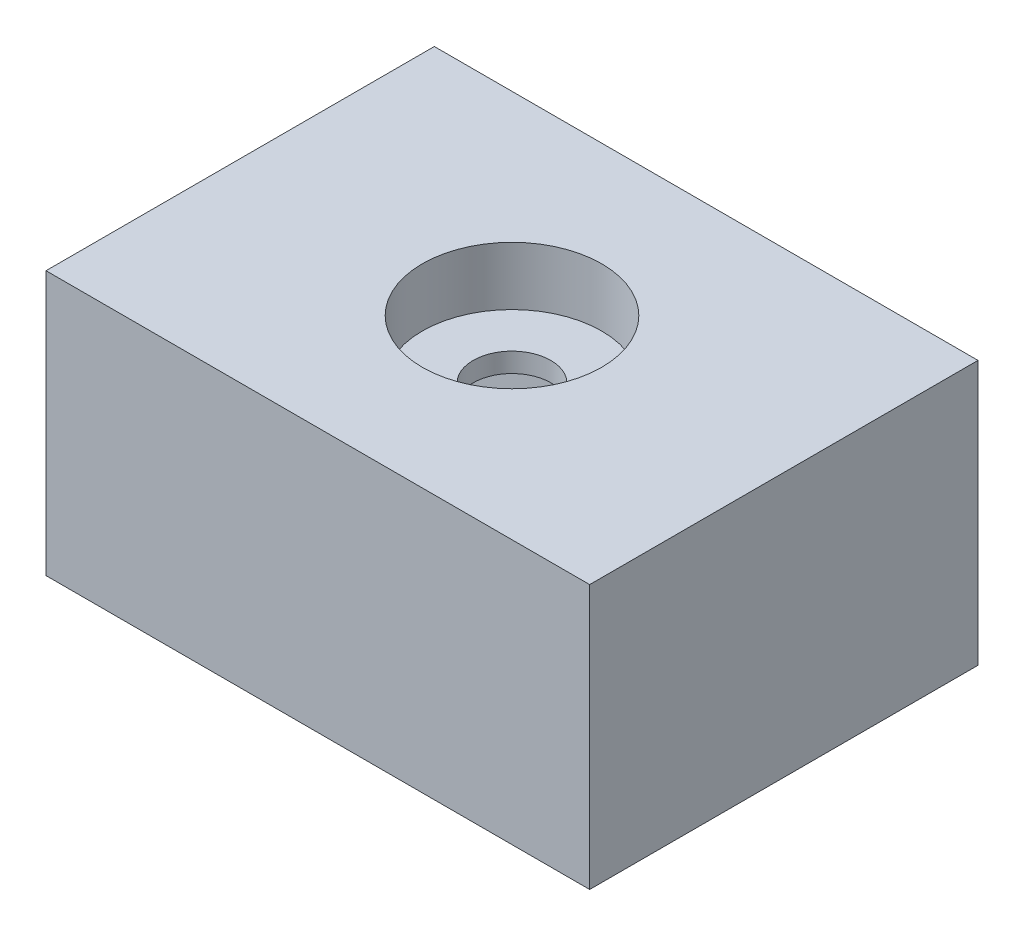
SolidWorks part; units mm, degrees
ref_plane "Front Plane" through (0, 0, 0) normal (0, 0, 1) x (1, 0, 0)
ref_plane "Top Plane" through (0, 0, 0) normal (0, 1, 0) x (1, 0, 0)
ref_plane "Right Plane" through (0, 0, 0) normal (1, 0, 0) x (0, 0, -1)
sketch "Sketch1" plane through (0, 0, 0) normal (0, 1, 0) x (1, 0, 0)
  line L1 (-88.9, 63.5) -> (88.9, 63.5)
  line L2 (-88.9, 63.5) -> (-88.9, -63.5)
  line L3 (-88.9, -63.5) -> (88.9, -63.5)
  line L4 (88.9, 63.5) -> (88.9, -63.5)
  line L5 (-88.9, 63.5) -> (88.9, -63.5) construction
  line L6 (-88.9, -63.5) -> (88.9, 63.5) construction
  point P0 (0, 0)
  dimension "D1" = 177.8
  dimension "D2" = 127
extrude "Boss-Extrude1" add sketch "Sketch1" along normal blind 86.36 contours L1 L4 L3 L2
sketch "Sketch2" plane through (0, 86.36, 0) normal (0, 1, 0) x (1, 0, 0)
  circle A0 centre (0, 0) radius 29.337
  dimension "D1" = 58.674
extrude "Cut-Extrude1" cut sketch "Sketch2" against normal blind 19.05 contours A0
shell "Shell1" thickness 6.35
sketch "Sketch4" plane through (0, 60.96, 0) normal (0, -1, 0) x (1, 0, 0)
  circle A0 centre (0, 0) radius 12.7
  dimension "D1" = 25.4
extrude "Cut-Extrude2" cut sketch "Sketch4" against normal up to surface (6.35 mm away) up to face at (0, 67.31, 29.337)
